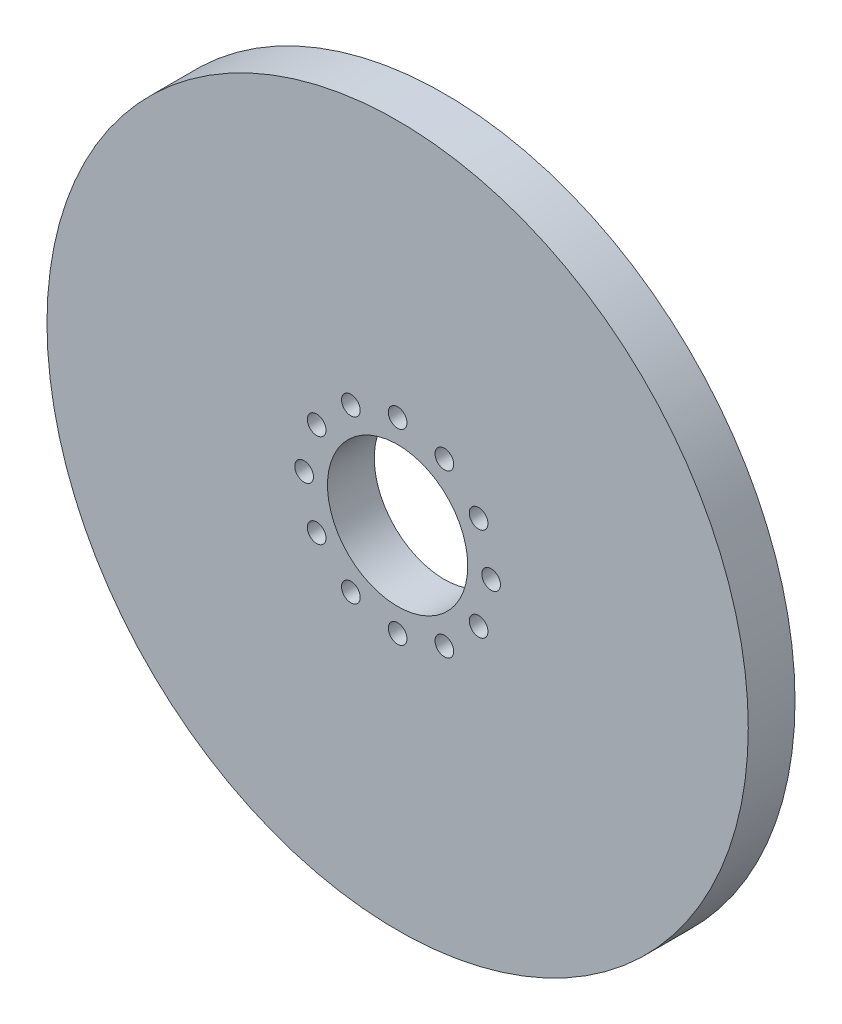
SolidWorks part; units mm, degrees
ref_plane "Ön Düzlem" through (0, 0, 0) normal (0, 0, 1) x (1, 0, 0)
ref_plane "Üst Düzlem" through (0, 0, 0) normal (0, 1, 0) x (1, 0, 0)
ref_plane "Sağ Düzlem" through (0, 0, 0) normal (1, 0, 0) x (0, 0, -1)
sketch "Sketch1" plane through (0, 0, 0) normal (0, 0, 1) x (1, 0, 0)
  circle A0 centre (0, 0) radius 150
  circle A1 centre (0, 0) radius 30
  circle A2 centre (0, 0) radius 40 construction
  circle A3 centre (0, 40) radius 4
  circle A4 centre (20, 34.641) radius 4
  circle A5 centre (34.641, 20) radius 4
  circle A6 centre (40, 0) radius 4
  circle A7 centre (34.641, -20) radius 4
  circle A8 centre (20, -34.641) radius 4
  circle A9 centre (0, -40) radius 4
  circle A10 centre (-20, -34.641) radius 4
  circle A11 centre (-34.641, -20) radius 4
  circle A12 centre (-40, 0) radius 4
  circle A13 centre (-34.641, 20) radius 4
  circle A14 centre (-20, 34.641) radius 4
  point P32 (0, 0)
  dimension "D1" = 300
  dimension "D2" = 60
  dimension "D3" = 80
  dimension "D4" = 8
  dimension "D5" = 12
extrude "Boss-Extrude1" add sketch "Sketch1" along normal blind 20
